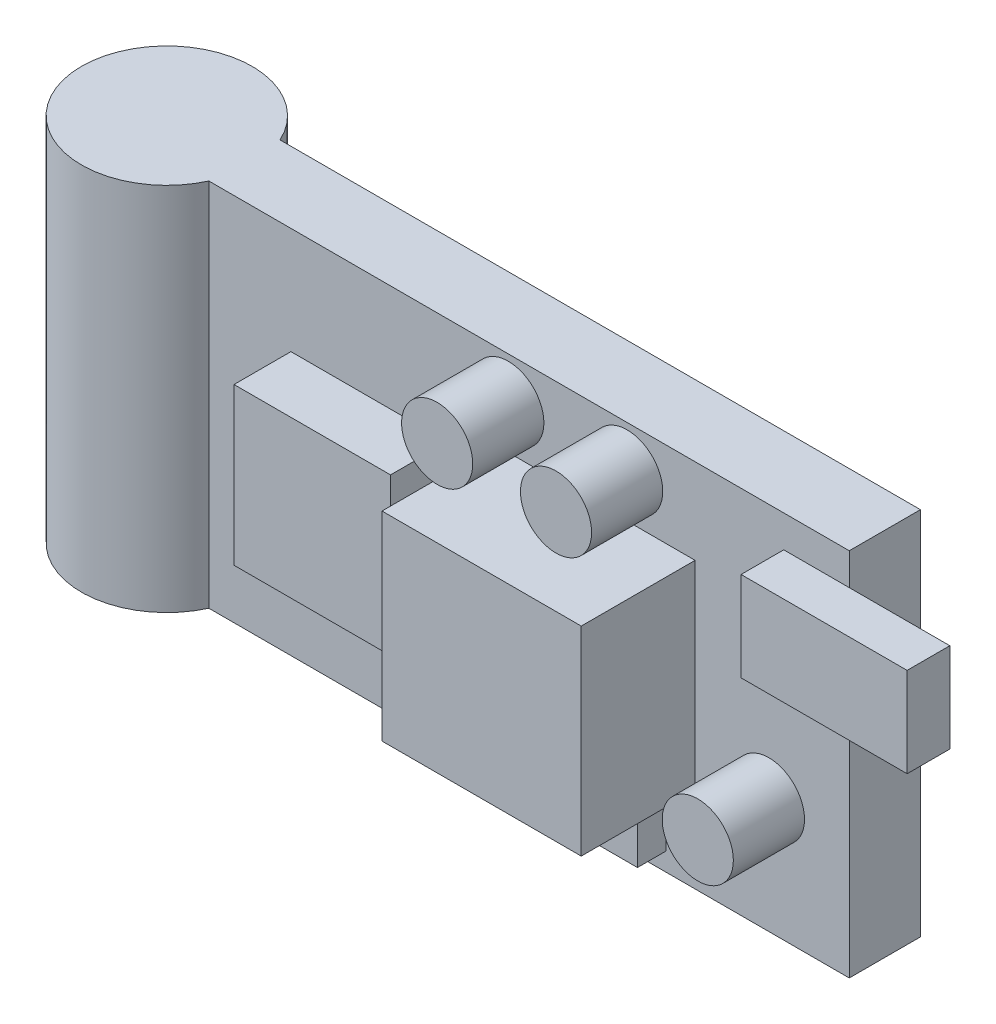
SolidWorks part; units mm, degrees
ref_plane "Спереди" through (0, 0, 0) normal (0, 0, 1) x (1, 0, 0)
ref_plane "Сверху" through (0, 0, 0) normal (0, 1, 0) x (1, 0, 0)
ref_plane "Справа" through (0, 0, 0) normal (1, 0, 0) x (0, 0, -1)
sketch "Эскиз1" plane through (0, 0, 0) normal (0, 0, 1) x (1, 0, 0)
  line L1 (-22.5, 13) -> (22.5, 13)
  line L2 (-22.5, 13) -> (-22.5, -13)
  line L3 (-22.5, -13) -> (22.5, -13)
  line L4 (22.5, 13) -> (22.5, -13)
  line L5 (-22.5, 13) -> (22.5, -13) construction
  line L6 (-22.5, -13) -> (22.5, 13) construction
  point P0 (0, 0)
  dimension "D1" = 45
  dimension "D2" = 26
extrude "Бобышка-Вытянуть1" add sketch "Эскиз1" along normal blind 5
sketch "Эскиз2" plane through (0, 13, 0) normal (0, 1, 0) x (1, 0, 0)
  line L0 (-22.5, -2.5) -> (-34.6185, -2.5) construction
  line L1 (-22.5, -5) -> (-22.5, 0) construction
  circle A0 centre (-27.9544, -2.5) radius 6
  dimension "D1" = 12
extrude "Бобышка-Вытянуть2" add sketch "Эскиз2" against normal up to surface (26 mm away) up to face at (0, -13, 2.5)
sketch "Эскиз3" plane through (0, 0, 5) normal (0, 0, 1) x (1, 0, 0)
  line L0 (22.5, 0) -> (-22.5, 0) construction
  line L1 (22.5, -13) -> (22.5, 13) construction
  line L2 (-22.5, 13) -> (-22.5, -13) construction
  line L4 (-2.3336, 7) -> (11.6664, 7)
  line L5 (-2.3336, 7) -> (-2.3336, -7)
  line L6 (-2.3336, -7) -> (11.6664, -7)
  line L7 (11.6664, 7) -> (11.6664, -7)
  line L8 (-2.3336, 7) -> (11.6664, -7) construction
  line L9 (-2.3336, -7) -> (11.6664, 7) construction
  point P6 (4.6664, 0)
  dimension "D1" = 14
  dimension "D2" = 14
extrude "Бобышка-Вытянуть3" add sketch "Эскиз3" along normal blind 8
sketch "Эскиз4" plane through (0, 0, 5) normal (0, 0, 1) x (1, 0, 0)
  circle A0 centre (-1.4584, 10.0533) radius 2.5
  circle A1 centre (6.8936, 10.0533) radius 2.5
  circle A2 centre (16.8541, -4.9184) radius 2.5
  dimension "D1" = 5
  dimension "D2" = 5
  dimension "D3" = 5
extrude "Бобышка-Вытянуть4" add sketch "Эскиз4" along normal blind 5
sketch "Эскиз5" plane through (0, 0, 5) normal (0, 0, 1) x (1, 0, 0)
  line L0 (22.5, 0) -> (-22.5, 0) construction
  line L1 (-16.7333, 5.5) -> (-5.7333, 5.5)
  line L2 (-16.7333, 5.5) -> (-16.7333, -5.5)
  line L3 (-16.7333, -5.5) -> (-5.7333, -5.5)
  line L4 (-5.7333, 5.5) -> (-5.7333, -5.5)
  line L5 (-16.7333, 5.5) -> (-5.7333, -5.5) construction
  line L6 (-16.7333, -5.5) -> (-5.7333, 5.5) construction
  point P0 (-11.2333, 0)
  dimension "D1" = 11
  dimension "D2" = 11
extrude "Бобышка-Вытянуть5" add sketch "Эскиз5" along normal blind 4
sketch "Эскиз6" plane through (0, 0, 5) normal (0, 0, 1) x (1, 0, 0)
  line L1 (-5.3731, -8.132) -> (0.8136, -8.132)
  line L2 (-5.3731, -8.132) -> (-5.3731, -11.7203)
  line L3 (-5.3731, -11.7203) -> (0.8136, -11.7203)
  line L4 (0.8136, -8.132) -> (0.8136, -11.7203)
  line L5 (-5.3731, -8.132) -> (0.8136, -11.7203) construction
  line L6 (-5.3731, -11.7203) -> (0.8136, -8.132) construction
  line L7 (3.5537, -8.132) -> (9.6167, -8.132)
  line L8 (3.5537, -8.132) -> (3.5537, -11.7203)
  line L9 (3.5537, -11.7203) -> (9.6167, -11.7203)
  line L10 (9.6167, -8.132) -> (9.6167, -11.7203)
  line L11 (3.5537, -8.132) -> (9.6167, -11.7203) construction
  line L12 (3.5537, -11.7203) -> (9.6167, -8.132) construction
  point P0 (-2.2797, -9.9261)
  point P5 (6.5852, -9.9261)
extrude "Бобышка-Вытянуть6" add sketch "Эскиз6" along normal blind 2
sketch "Эскиз7" plane through (0, 0, 5) normal (0, 0, 1) x (1, 0, 0)
  line L1 (17.8959, 10.754) -> (29.565, 10.754)
  line L2 (17.8959, 10.754) -> (17.8959, 4.4627)
  line L3 (17.8959, 4.4627) -> (29.565, 4.4627)
  line L4 (29.565, 10.754) -> (29.565, 4.4627)
  line L5 (17.8959, 10.754) -> (29.565, 4.4627) construction
  line L6 (17.8959, 4.4627) -> (29.565, 10.754) construction
  point P0 (23.7305, 7.6084)
extrude "Бобышка-Вытянуть7" add sketch "Эскиз7" along normal blind 3
